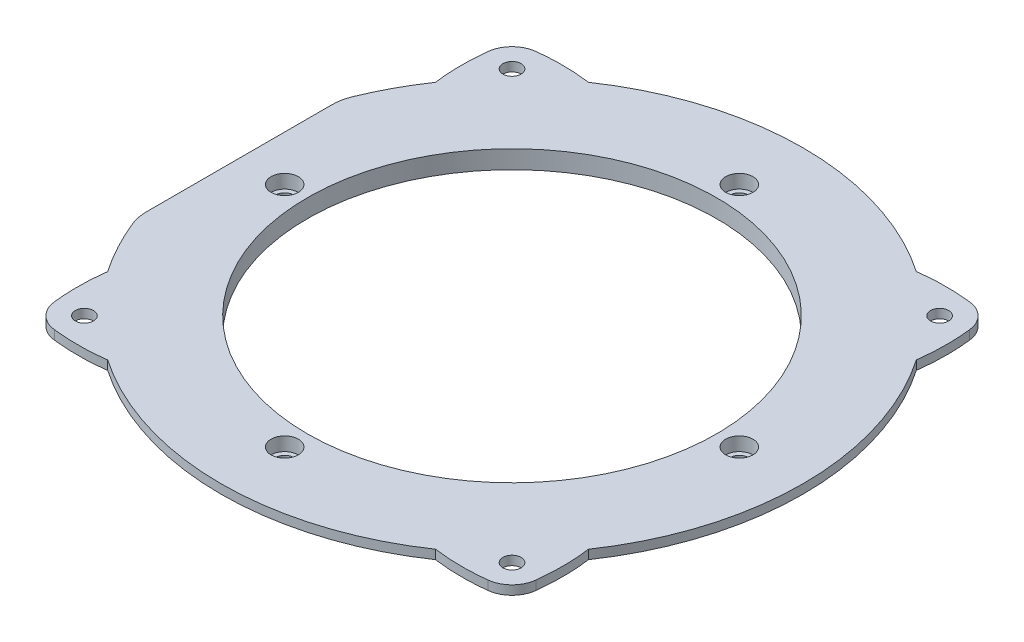
SolidWorks part; units mm, degrees
ref_plane "前视基准面" through (0, 0, 0) normal (0, 0, 1) x (1, 0, 0)
ref_plane "上视基准面" through (0, 0, 0) normal (0, 1, 0) x (1, 0, 0)
ref_plane "右视基准面" through (0, 0, 0) normal (1, 0, 0) x (0, 0, -1)
other "Configuration Table"
sketch "草图1" plane through (0, 0, 0) normal (0, 1, 0) x (1, 0, 0)
  line L0 (0, 72.8796) -> (0, -65.2671) construction
  line L1 (-66.7119, 0) -> (65.0587, 0) construction
  circle A0 centre (0, 0) radius 50 construction
  circle A1 centre (0, 0) radius 45
  circle A2 centre (0, 0) radius 55
  dimension "D1" = 100
  dimension "D2" = 90
  dimension "D3" = 110
extrude "凸台-拉伸1" add sketch "草图1" against normal blind 4
sketch "草图2" plane through (0, -4, 0) normal (0, -1, 0) x (-1, 0, 0)
  line L0 (0, 76.7235) -> (0, -70.692) construction
  line L1 (-78.1199, 0) -> (76.9236, 0) construction
  circle A0 centre (0, 0) radius 60 construction
  circle A1 centre (0, 0) radius 64
  circle A2 centre (0, 0) radius 55 construction
  circle A3 centre (0, 0) radius 55
  dimension "D1" = 120
  dimension "D2" = 128
extrude "凸台-拉伸2" add sketch "草图2" along normal blind 2 from offset 4 offset against normal yes
sketch "草图3" plane through (0, 0, 0) normal (0, 1, 0) x (1, 0, 0)
  line L0 (0, 75.2586) -> (0, -69.0659) construction
  circle A0 centre (0, 0) radius 50 construction
  circle A1 centre (0, 50) radius 3
  dimension "D1" = 100
  dimension "D2" = 6
extrude "切除-拉伸1" cut sketch "草图3" against normal blind 3
pattern_circular "阵列(圆周)1" count 4 over 360 about axis through (0, 0, 0) along (0, 1, 0) of "切除-拉伸1"
sketch "草图4" plane through (0, -3, 0) normal (0, 1, 0) x (1, 0, 0)
  circle A0 centre (0, 50) radius 2
  dimension "D1" = 4
extrude "切除-拉伸2" cut sketch "草图4" against normal through all
pattern_circular "阵列(圆周)2" count 4 every 90 about axis through (0, 0, 0) along (0, 1, 0) of "切除-拉伸2"
sketch "草图5" plane through (0, 0, 0) normal (0, 1, 0) x (1, 0, 0)
  line L0 (0, 0) -> (0, 78.8921) construction
  line L1 (0, 0) -> (62.2856, 62.2856) construction
  line L2 (0, 0) -> (82.5654, 0) construction
  circle A0 centre (0, 0) radius 66.5 construction
  circle A1 centre (47.0226, 47.0226) radius 2
  circle A2 centre (0, 0) radius 64 construction
  arc A3 (47.7058, 52.9714) -> (52.9714, 47.7058) centre (47.0117, 47.0117) cw
  arc A4 (52.9714, -47.7058) -> (47.7058, -52.9714) centre (47.0117, -47.0117) cw
  circle A5 centre (47.0226, -47.0226) radius 2
  arc A6 (-47.7058, -52.9714) -> (-52.9714, -47.7058) centre (-47.0117, -47.0117) cw
  circle A7 centre (-47.0226, -47.0226) radius 2
  arc A8 (-52.9714, 47.7058) -> (-47.7058, 52.9714) centre (-47.0117, 47.0117) cw
  circle A9 centre (-47.0226, 47.0226) radius 2
  arc A10 (-36.0575, 52.8759) -> (-52.8759, 36.0575) centre (0, 0) ccw
  arc A11 (-52.8759, -36.0575) -> (-36.0575, -52.8759) centre (0, 0) ccw
  arc A12 (36.0575, -52.8759) -> (52.8759, -36.0575) centre (0, 0) ccw
  arc A13 (52.8759, 36.0575) -> (36.0575, 52.8759) centre (0, 0) ccw
  spline S0 degree 3 poles (36.0575, 52.8759) (39.8422, 53.4003) (43.8553, 53.4199) (47.7058, 52.9714) knots 0 0 0 0 0.71826 0.71826 0.71826 0.71826
  spline S1 degree 3 poles (52.8759, 36.0575) (53.4003, 39.8422) (53.4199, 43.8553) (52.9714, 47.7058) knots 0 0 0 0 0.71826 0.71826 0.71826 0.71826
  spline S2 degree 3 poles (52.8759, -36.0575) (53.4003, -39.8422) (53.4199, -43.8553) (52.9714, -47.7058) knots 0 0 0 0 0.71826 0.71826 0.71826 0.71826
  spline S3 degree 3 poles (36.0575, -52.8759) (39.8422, -53.4003) (43.8553, -53.4199) (47.7058, -52.9714) knots 0 0 0 0 0.71826 0.71826 0.71826 0.71826
  spline S4 degree 3 poles (-36.0575, -52.8759) (-39.8422, -53.4003) (-43.8553, -53.4199) (-47.7058, -52.9714) knots 0 0 0 0 0.71826 0.71826 0.71826 0.71826
  spline S5 degree 3 poles (-52.8759, -36.0575) (-53.4003, -39.8422) (-53.4199, -43.8553) (-52.9714, -47.7058) knots 0 0 0 0 0.71826 0.71826 0.71826 0.71826
  spline S6 degree 3 poles (-52.8759, 36.0575) (-53.4003, 39.8422) (-53.4199, 43.8553) (-52.9714, 47.7058) knots 0 0 0 0 0.71826 0.71826 0.71826 0.71826
  spline S7 degree 3 poles (-36.0575, 52.8759) (-39.8422, 53.4003) (-43.8553, 53.4199) (-47.7058, 52.9714) knots 0 0 0 0 0.71826 0.71826 0.71826 0.71826
  point P47 (0, 0)
  dimension "D2" = 133
  dimension "D3" = 4
  dimension "D4" = 6
  dimension "D1" = 45
  dimension "D5" = 4
extrude "凸台-拉伸3" add sketch "草图5" against normal blind 2
sketch "草图6" plane through (0, 0, 0) normal (0, 1, 0) x (1, 0, 0)
  line L0 (-60, 26.7144) -> (-60, -26.6451)
  line L1 (-60, 58) -> (-60, -58) construction
  line L2 (-60, -26.6451) -> (-76.4143, -26.6451)
  line L3 (-76.4143, -26.6451) -> (-74.8939, 32.8099)
  line L4 (-74.8939, 32.8099) -> (-60, 26.7144)
extrude "切除-拉伸3" cut sketch "草图6" against normal through all both and the other way through all
fillet "圆角1" radius 10 2 edges at (-60, -1, -22.2711) (-60, -1, 22.2711)
